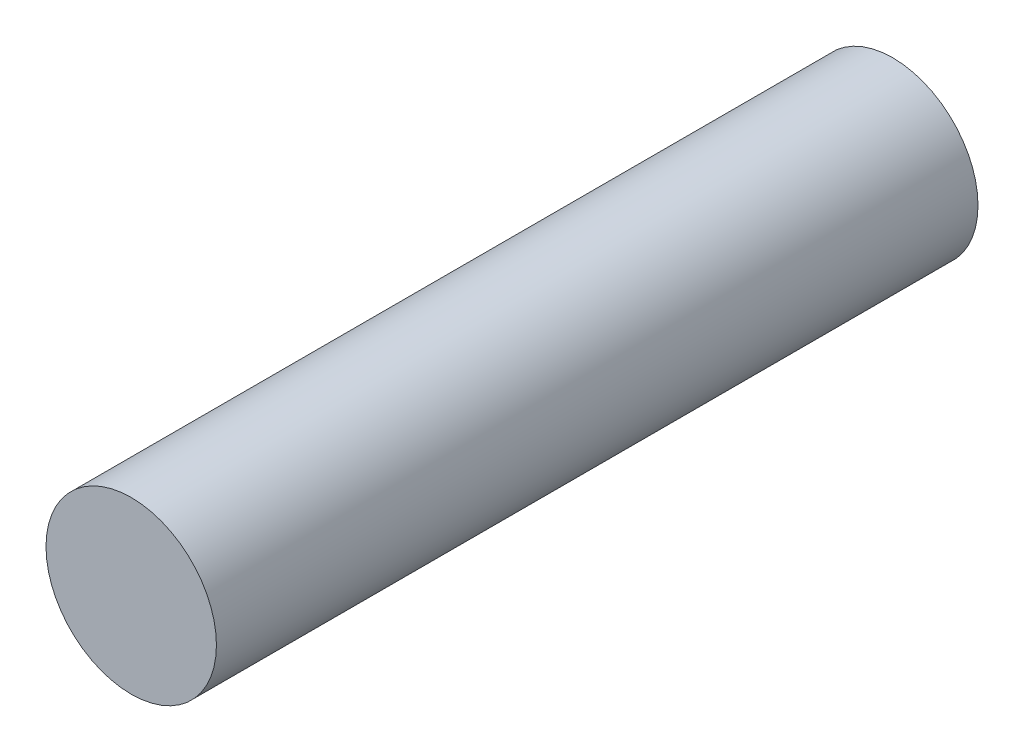
SolidWorks part; units mm, degrees
ref_plane "Front Plane" through (0, 0, 0) normal (0, 0, 1) x (1, 0, 0)
ref_plane "Top Plane" through (0, 0, 0) normal (0, 1, 0) x (1, 0, 0)
ref_plane "Right Plane" through (0, 0, 0) normal (1, 0, 0) x (0, 0, -1)
sketch "Sketch1" plane through (0, 0, 0) normal (0, 0, 1) x (1, 0, 0)
  circle A0 centre (0, 0) radius 2.7
  dimension "D1" = 5.4
extrude "Boss-Extrude1" add sketch "Sketch1" along normal blind 24.13
